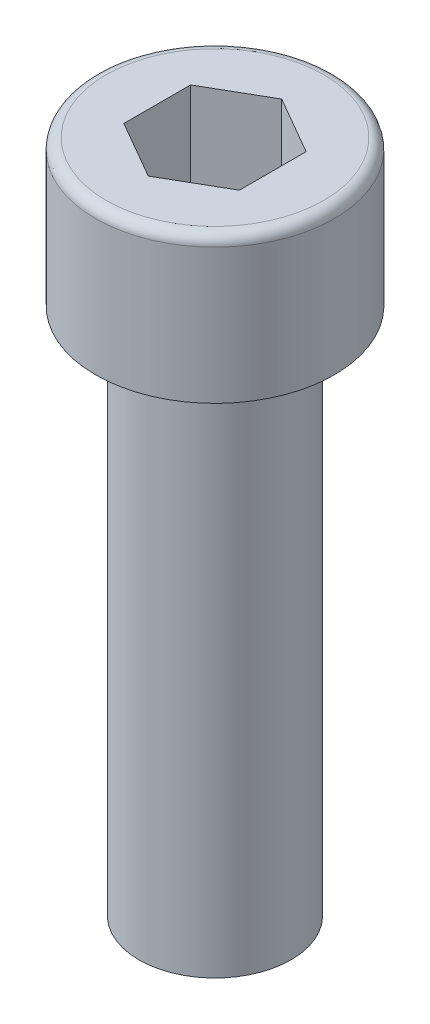
SolidWorks part; units mm, degrees
ref_plane "Front Plane" through (0, 0, 0) normal (0, 0, 1) x (1, 0, 0)
ref_plane "Top Plane" through (0, 0, 0) normal (0, 1, 0) x (1, 0, 0)
ref_plane "Right Plane" through (0, 0, 0) normal (1, 0, 0) x (0, 0, -1)
sketch "Sketch1" plane through (0, 0, 0) normal (0, 1, 0) x (1, 0, 0)
  circle A0 centre (0, 0) radius 1.8288
  dimension "D1" = 3.6576
extrude "Boss-Extrude1" add sketch "Sketch1" against normal blind 12.7
sketch "Sketch2" plane through (0, 0, 0) normal (0, 1, 0) x (1, 0, 0)
  circle A0 centre (0, 0) radius 2.8702
  dimension "D1" = 5.7404
extrude "Boss-Extrude2" add sketch "Sketch2" along normal blind 3.5052
fillet "Fillet1" radius 0.254 1 edges at (0, 3.5052, 2.8702)
sketch "Sketch3" plane through (0, 3.5052, 0) normal (0, 1, 0) x (1, 0, 0)
  line L1 (0, 1.604) -> (-1.3891, 0.802)
  line L2 (-1.3891, 0.802) -> (-1.3891, -0.802)
  line L3 (-1.3891, -0.802) -> (0, -1.604)
  line L4 (0, -1.604) -> (1.3891, -0.802)
  line L5 (1.3891, -0.802) -> (1.3891, 0.802)
  line L6 (1.3891, 0.802) -> (0, 1.604)
  circle A0 centre (0, 0) radius 1.3891 construction
  dimension "D1" = 2.7781
extrude "Cut-Extrude1" cut sketch "Sketch3" against normal blind 2.54
